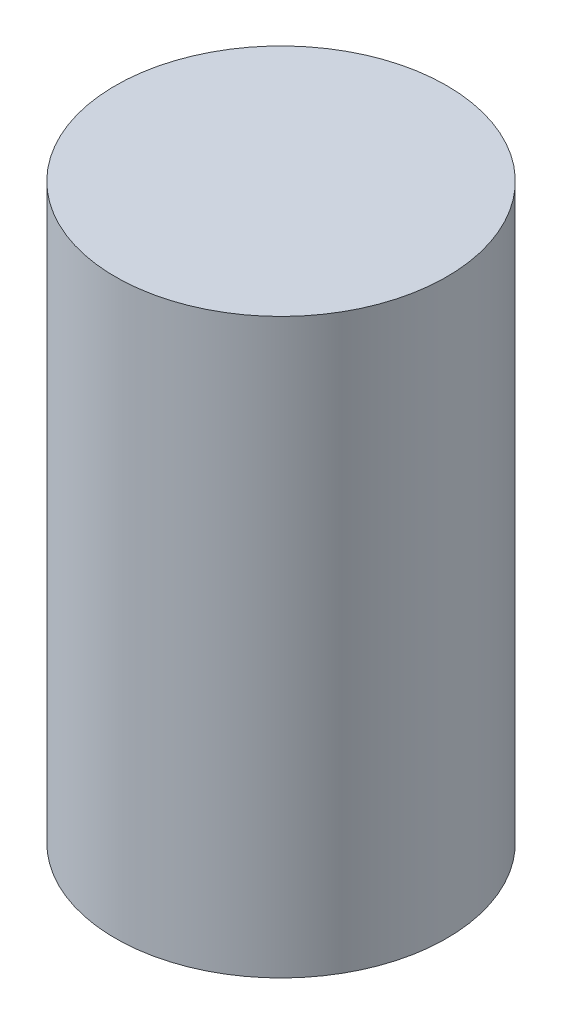
SolidWorks part; units mm, degrees
ref_plane "Front Plane" through (0, 0, 0) normal (0, 0, 1) x (1, 0, 0)
ref_plane "Top Plane" through (0, 0, 0) normal (0, 1, 0) x (1, 0, 0)
ref_plane "Right Plane" through (0, 0, 0) normal (1, 0, 0) x (0, 0, -1)
sketch "Sketch1" plane through (0, 0, 0) normal (0, 1, 0) x (1, 0, 0)
  circle A0 centre (0, 0) radius 4.8
  dimension "D1" = 9.6
extrude "Boss-Extrude1" add sketch "Sketch1" along normal blind 16.6
